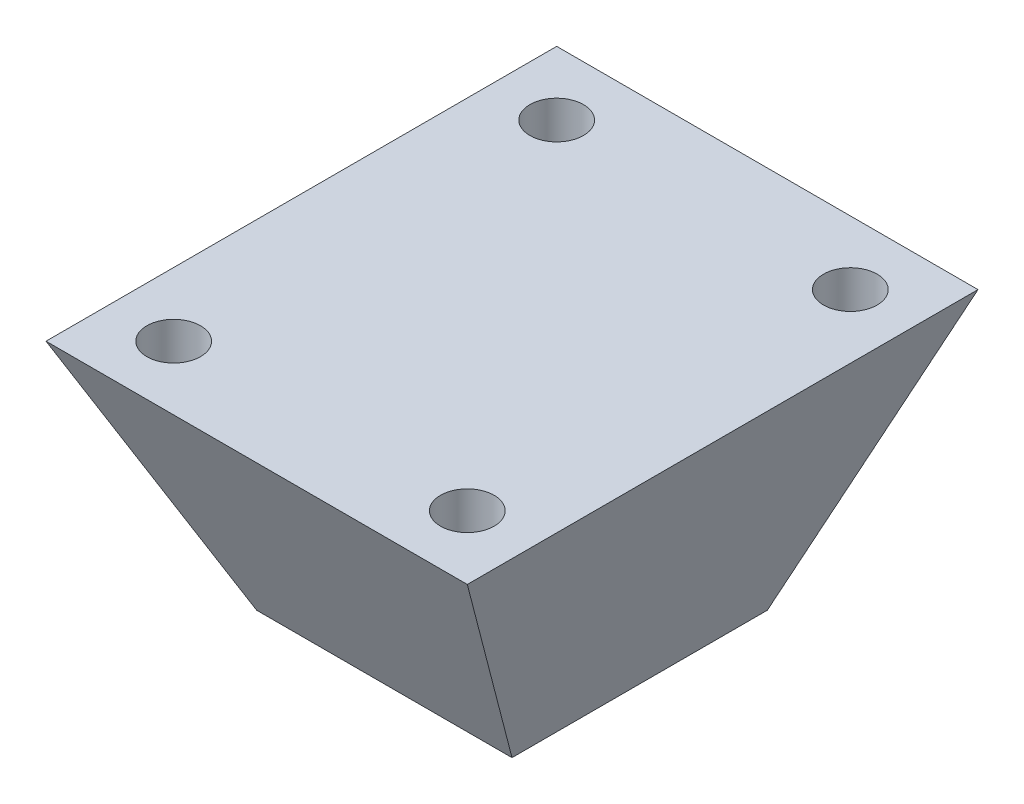
SolidWorks part; units mm, degrees
ref_plane "Front Plane" through (0, 0, 0) normal (0, 0, 1) x (1, 0, 0)
ref_plane "Top Plane" through (0, 0, 0) normal (0, 1, 0) x (1, 0, 0)
ref_plane "Right Plane" through (0, 0, 0) normal (1, 0, 0) x (0, 0, -1)
sketch "Sketch1" plane through (0, 0, 0) normal (0, 1, 0) x (1, 0, 0)
  line L0 (0, -10) -> (0, 10)
  line L1 (0, 0) -> (-10, 0) construction
  line L2 (-10, 10) -> (0, 10)
  line L3 (-10, 10) -> (10, 10)
  line L4 (-10, 10) -> (-10, -10)
  line L5 (-10, -10) -> (10, -10)
  line L6 (0, 10) -> (0, -10)
  line L7 (-10, -10) -> (0, -10)
  line L8 (10, 10) -> (10, -10)
  line L9 (0, 0) -> (0, 5) construction
  line L10 (0, 5) -> (-5, 5) construction
  circle A1 centre (-5, 5) radius 2.1
  circle A2 centre (-5, -5) radius 2.1
  circle A3 centre (5, 5) radius 2.1
  circle A4 centre (5, -5) radius 2.1
  point P4 (0, 0)
ref_plane "Plane1" through (0, 20, 0) normal (0, 1, 0) x (1, 0, 0)
sketch "Sketch2" plane through (0, 20, 0) normal (0, 1, 0) x (1, 0, 0)
  line L0 (0, -20) -> (0, 20)
  line L2 (-16.5, 20) -> (16.5, 20)
  line L4 (-16.5, 20) -> (16.5, 20)
  line L5 (-16.5, 20) -> (-16.5, -20)
  line L6 (-16.5, -20) -> (16.5, -20)
  line L7 (16.5, 20) -> (16.5, -20)
  point P4 (0, 0)
  point P8 (0, 20)
  point P10 (0, 0)
ref_plane "Plane2" through (9.0447, -2.9395, 0) normal (-0.951, 0.3091, 0) x (0, 0, 1)
sketch "Sketch4" plane through (9.0447, -2.9395, 0) normal (-0.951, 0.3091, 0) x (0, 0, 1)
  line L1 (-21.9452, 1.5583) -> (-22.817, 25.4204)
  line L2 (-22.817, 25.4204) -> (26.4911, 25.4204)
  line L3 (26.4911, 25.4204) -> (24.9427, 1.5583)
  line L4 (24.9427, 1.5583) -> (-21.9452, 1.5583)
  point P0 (26.4911, 25.4204)
ref_plane "Plane3" through (0, -4, -8) normal (0, 0.4472, 0.8944) x (1, 0, 0)
sketch "Sketch5" plane through (0, -4, -8) normal (0, 0.4472, 0.8944) x (1, 0, 0)
  line L5 (-21.3597, 30.4364) -> (24.8476, 30.4364)
  line L6 (-21.3597, 30.4364) -> (-21.3597, -11.4446)
  line L7 (-21.3597, -11.4446) -> (24.8476, -11.4446)
  line L8 (24.8476, 30.4364) -> (24.8476, -11.4446)
extrude "Boss-Extrude1" add sketch "Sketch2" against normal blind 20 contours L5 L6 L0 L2 | L7 L2 L0 L6
extrude "Cut-Extrude1" cut sketch "Sketch4" against normal blind 20
extrude "Cut-Extrude2" cut sketch "Sketch5" against normal blind 20
mirror "Mirror1" about plane through (0, 0, 0) normal (0, 0, 1) of "Cut-Extrude2"
mirror "Mirror2" about plane through (0, 0, 0) normal (1, 0, 0) of "Cut-Extrude1"
extrude "Cut-Extrude3" cut sketch "Sketch1" along normal blind 5.7 contours A1 | A3 | A4 | A2
sketch "Sketch7" plane through (0, 20, 0) normal (0, 1, 0) x (1, 0, 0)
  line L0 (0, 0) -> (0, 15) construction
  line L1 (0, 15) -> (-11.5, 15) construction
  line L2 (0, 0) -> (-11.5, 0) construction
  circle A0 centre (-11.5, 15) radius 2.1
  circle A1 centre (-11.5, -15) radius 2.1
  circle A2 centre (11.5, -15) radius 2.1
  circle A3 centre (11.5, 15) radius 2.1
extrude "Cut-Extrude4" cut sketch "Sketch7" against normal blind 5.7
